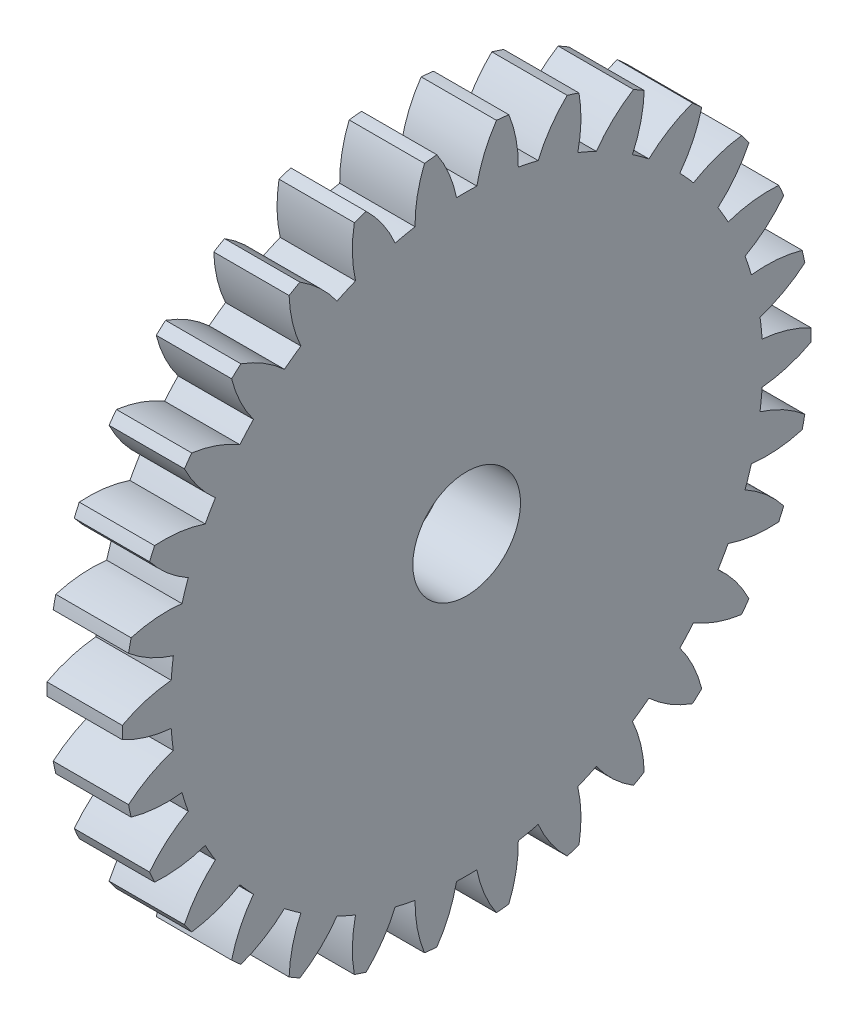
SolidWorks part; units mm, degrees
material "Cedar"
ref_plane "Plane1" through (0, 0, 0) normal (0, 0, 1) x (1, 0, 0)
ref_plane "Plane2" through (0, 0, 0) normal (0, 1, 0) x (1, 0, 0)
ref_plane "Plane3" through (0, 0, 0) normal (1, 0, 0) x (0, 0, -1)
sketch "HoldingSke" plane through (0, 0, 0) normal (0, 1, 0) x (1, 0, 0)
  line L0 (0, 0) -> (439.9409, -254)
  line L1 (-15, 0) -> (100, 0) construction
  line L2 (0, 0) -> (-2.1039, 2.3779)
  line L3 (0, 0) -> (-11.863, 4.5341)
  line L4 (0, 0) -> (7.479, 4.318)
  line L5 (0, 0) -> (-47.5972, -17.7524)
  line L6 (0, 0) -> (-3.6847, -2.4861)
  line L7 (-2.1039, 2.3779) -> (8.8308, 51.9871)
  line L8 (-76.2, 54.61) -> (-69.596, 54.61)
  line L9 (-71.009, 38.7566) -> (-53.1078, 45.2721)
  line L10 (-76.2, 71.12) -> (104.1128, 71.12)
  line L11 (0, 0) -> (-4.445, 0)
  line L12 (-76.2, 101.6) -> (-76.1492, 101.6)
  line L13 (24.9733, 27.94) -> (52.9518, 28.4284)
  line L14 (24.9733, 27.94) -> (25.0241, 27.9398)
  line L15 (24.9733, 27.94) -> (100.4021, 29.52)
  circle A0 centre (0, 0) radius 3.175
  circle A1 centre (0, 0) radius 17.4752
  circle A2 centre (0, 0) radius 38.1
  circle A3 centre (0, 0) radius 3.175
  dimension "MHD" = 34.9504
  dimension "Hub_dia" = 76.2
  dimension "Bore" = 6.35
  dimension "MBD" = 6.35
  dimension "Num_teeth" = 30
  dimension "Pitch_radius" = 180.3128
  dimension "Pitch" = 508
  dimension "Width" = 4.445
  dimension "Overall_len" = 50.8
  dimension "Show_teeth" = 30
  dimension "Thickness" = 4.445
  dimension "OAL" = 50.8001
  dimension "T_dim" = 6.604
  dimension "Ap" = 20
  dimension "H" = 19.05
  dimension "Backlash" = 0.0508
  dimension "Addendum_fac" = 1
  dimension "Dedendum_fac" = 1.2
  dimension "Clearance_fac" = 0.2
  dimension "Dedendum_add" = 0.0508
sketch "BasProSke" plane through (0, 0, 0) normal (0, 1, 0) x (1, 0, 0)
  line L0 (-10, 0) -> (60, 0) construction
  line L1 (0, 0) -> (0, 20.32)
  line L2 (0, 0) -> (4.445, 0)
  line L3 (4.445, 0) -> (4.445, 20.32)
  line L4 (4.445, 20.32) -> (0, 20.32)
  dimension "Diameter" = 40.64
  dimension "Thickness" = 4.445
revolve "Base-Revolve" add sketch "BasProSke" angle 360 about L0
sketch "TooCutSke" plane through (0, 0, 0) normal (1, 0, 0) x (0, 0, -1)
  line L1 (0, 0) -> (0, 107) construction
  line L2 (0, 0) -> (-1.0859, 19.019) construction
  line L3 (0, 0) -> (-3.978, 37.8482) construction
  line L4 (-1.0859, 19.019) -> (-1.989, 18.9241) construction
  arc A0 (0.5992, 17.4649) -> (-0.5992, 17.4649) centre (0, 0) ccw
  arc A1 (1.7751, 20.2678) -> (-1.7751, 20.2678) centre (0, 0) ccw
  circle A2 centre (0, 0) radius 19.05 construction
  circle A3 centre (0, 0) radius 17.9011 construction
  arc A4 (-0.5992, 17.4649) -> (-1.7751, 20.2678) centre (-8.0726, 15.9776) ccw
  arc A5 (1.7751, 20.2678) -> (0.5992, 17.4649) centre (8.0726, 15.9776) ccw
  dimension "Root_dia" = 34.9504
  dimension "Overcut_dia" = 40.6908
  dimension "Pitch_dia" = 38.1
  dimension "Base_dia" = 35.8023
  dimension "Flank_rad" = 7.62
  dimension "Half_ang" = 6
  dimension "Half_CT" = 0.9081
extrude "ToothCut" cut sketch "TooCutSke" along normal through all
fillet "Breaks" [suppressed] radius 0.0254
fillet "RootFillets" [suppressed] radius 0.3048
pattern_circular "TeethCuts" count 30 every 12 about axis through (-10, 0, 0) along (1, 0, 0) of "ToothCut", "RootFillets", "Breaks"
sketch "HubNeaOneSke" plane through (0, 0, 0) normal (-1, 0, 0) x (0, 0, 1)
  circle A0 centre (0, 0) radius 17.4752
  dimension "Diameter" = 34.9504
extrude "HubNearOne" [suppressed] add sketch "HubNeaOneSke" along normal blind 46.3551
sketch "HubNeaBotSke" plane through (0, 0, 0) normal (-1, 0, 0) x (0, 0, 1)
  circle A0 centre (0, 0) radius 17.4752
  dimension "Diameter" = 34.9504
extrude "HubNearBoth" [suppressed] add sketch "HubNeaBotSke" along normal blind 23.1775
ref_plane "FarPln" through (4.445, 0, 0) normal (1, 0, 0) x (0, 0, -1)
sketch "HubFarSke" plane through (4.445, 0, 0) normal (1, 0, 0) x (0, 0, -1)
  circle A0 centre (0, 0) radius 17.4752
  dimension "Diameter" = 34.9504
extrude "HubFar" [suppressed] add sketch "HubFarSke" along normal blind 23.1775
sketch "BorSke" plane through (0, 0, 0) normal (1, 0, 0) x (0, 0, -1)
  circle A0 centre (0, 0) radius 3.175
  dimension "Diameter" = 6.35
extrude "Bore" cut sketch "BorSke" along normal mid plane 101.6001
sketch "KeySke" plane through (0, 0, 0) normal (1, 0, 0) x (0, 0, -1)
  line L0 (-0.127, 0) -> (-0.127, 3.429)
  line L1 (-0.127, 3.429) -> (0.127, 3.429)
  line L2 (0.127, 3.429) -> (0.127, 0)
  line L3 (0, 0) -> (0, 34) construction
  line L4 (-0.127, 0) -> (0.127, 0)
  dimension "Offset" = 3.429
  dimension "Width" = 0.254
extrude "Keyway" [suppressed] cut sketch "KeySke" along normal mid plane 101.6001
pattern_circular "Keyway2" [suppressed] count 2 every 90 about axis through (-10, 0, 0) along (1, 0, 0)
sketch "Sketch2" plane through (0, 0, 0) normal (-1, 0, 0) x (0, 0, 1)
  circle A0 centre (0, 0) radius 19.05
  dimension "D1" = 38.1
equation "' \"Pitch@HoldingSke\" = 4"
equation "' \"Num_teeth@HoldingSke\" = 12"
equation "' \"Ap@HoldingSke\" =  20"
equation "' \"Width@HoldingSke\" = 0.5"
equation "' \"Hub_dia@HoldingSke\"= 1"
equation "' \"Overall_len@HoldingSke\" = 1.0"
equation "' \"Bore@HoldingSke\" = 0.75"
equation "' \"T_dim@HoldingSke\" = 0.85"
equation "' \"Width@KeySke\" = 0.25"
equation "' \"Show_teeth@HoldingSke\" = 13"
equation "' \"Backlash@HoldingSke\" = 0.009"
equation "' \"Addendum_fac@HoldingSke\" = 1.0"
equation "' \"Dedendum_fac@HoldingSke\" = 1.25"
equation "' \"Dedendum_add@HoldingSke\" = 0.00005"
equation "' \"Clearance_fac@HoldingSke\" = 0.25"
equation "' \"Pitch@HoldingSke\" = 0.5"
equation "' \"Num_teeth@HoldingSke\" = 23"
equation "' \"Show_teeth@HoldingSke\" = 23"
equation "' \"Backlash@HoldingSke\" = 0.0375"
equation "\"Overcut_dia@TooCutSke\" = (\"Num_teeth@HoldingSke\" + 2 * \"Addendum_fac@HoldingSke\") / \"Pitch@HoldingSke\" + 0.002"
equation "\"Pitch_dia@TooCutSke\" = \"Num_teeth@HoldingSke\" / \"Pitch@HoldingSke\""
equation "\"Base_dia@TooCutSke\" = \"Num_teeth@HoldingSke\" / \"Pitch@HoldingSke\" * cos((\"Ap@HoldingSke\"  * 3.14159265 / 180))"
equation "\"Root_dia@TooCutSke\" = (\"Num_teeth@HoldingSke\" + 2) / \"Pitch@HoldingSke\" - 2 * (\"Addendum_fac@HoldingSke\" + \"Dedendum_fac@HoldingSke\") / \"Pitch@HoldingSke\" - \"Dedendum_add@HoldingSke\" * 2"
equation "\"Half_ang@TooCutSke\" = 180 / \"Num_teeth@HoldingSke\""
equation "\"Half_CT@TooCutSke\" = \"Num_teeth@HoldingSke\" / \"Pitch@HoldingSke\" * sin((3.14159265 / 2 / \"Num_teeth@HoldingSke\")) / 2 - 7 * \"Backlash@HoldingSke\" / 4"
equation "\"Flank_rad@TooCutSke\" = \"Num_teeth@HoldingSke\" / \"Pitch@HoldingSke\" / 5"
equation "\"Radius@RootFillets\" = \"Clearance_fac@HoldingSke\" / \"Pitch@HoldingSke\" + \"Dedendum_add@HoldingSke\""
equation "\"Break_rad@Breaks\" = 0.02 / \"Pitch@HoldingSke\""
equation "\"Thickness@HoldingSke\" = \"Width@HoldingSke\""
equation "\"OAL@HoldingSke\" = \"Thickness@HoldingSke\""
equation "\"MHD@HoldingSke\" = (\"Num_teeth@HoldingSke\" + 2) / \"Pitch@HoldingSke\" - 2 * (\"Addendum_fac@HoldingSke\" + \"Dedendum_fac@HoldingSke\")  / \"Pitch@HoldingSke\" - \"Dedendum_add@HoldingSke\" * 2"
equation "\"MBD@HoldingSke\" = (\"Num_teeth@HoldingSke\" + 2) / \"Pitch@HoldingSke\" - 2 * (\"Addendum_fac@HoldingSke\" + \"Dedendum_fac@HoldingSke\")  / \"Pitch@HoldingSke\" - \"Dedendum_add@HoldingSke\" * 2 - 0.002"
equation "\"MHD@HoldingSke\" = ((sgn( \"MHD@HoldingSke\" - \"Hub_dia@HoldingSke\" )-1)*( \"MHD@HoldingSke\" - \"Hub_dia@HoldingSke\" ))/-2+ \"Hub_dia@HoldingSke\""
equation "\"MBD@HoldingSke\" = ((sgn( \"MBD@HoldingSke\" - \"Bore@HoldingSke\" )-1)*( \"MBD@HoldingSke\" - \"Bore@HoldingSke\" ))/-2+ \"Bore@HoldingSke\""
equation "\"OAL@HoldingSke\" = ((sgn( \"OAL@HoldingSke\" - \"Overall_len@HoldingSke\" )+1)*( \"OAL@HoldingSke\" - \"Overall_len@HoldingSke\" ))/2 + \"Overall_len@HoldingSke\" + 0.000002"
equation "\"Num_teeth@TeethCuts\" = int( \"Show_teeth@HoldingSke\" ) + 1"
equation "\"Num_teeth@TeethCuts\" = ((sgn( \"Num_teeth@TeethCuts\" - \"Num_teeth@HoldingSke\" )-1)*( \"Num_teeth@TeethCuts\" - \"Num_teeth@HoldingSke\" ))/-2+ \"Num_teeth@HoldingSke\""
equation "\"Num_teeth@TeethCuts\" = ((sgn( \"Num_teeth@TeethCuts\" - 2.0)+1)*( \"Num_teeth@TeethCuts\" - 2.0))/2 +2.0"
equation "\"Angle@TeethCuts\" = 360.0 / \"Num_teeth@HoldingSke\""
equation "\"Diameter@BasProSke\" = (\"Num_teeth@HoldingSke\" + 2 * \"Addendum_fac@HoldingSke\") / \"Pitch@HoldingSke\""
equation "\"Thickness@BasProSke\"  = \"Thickness@HoldingSke\""
equation "' \"Fillet_rad@BasProSke\" =  \"Thickness@HoldingSke\" * 0.05"
equation "\"MHD@HoldingSke\" = ((sgn( \"MHD@HoldingSke\" - \"Root_dia@TooCutSke\" )-1)*( \"MHD@HoldingSke\" - \"Root_dia@TooCutSke\" ))/-2+ \"Root_dia@TooCutSke\""
equation "\"Diameter@HubNeaOneSke\" = \"MHD@HoldingSke\""
equation "\"Length@HubNearOne\" = \"OAL@HoldingSke\" - \"Thickness@BasProSke\""
equation "\"Diameter@HubNeaBotSke\" = \"MHD@HoldingSke\""
equation "\"Length@HubNearBoth\" = ( \"OAL@HoldingSke\" - \"Thickness@BasProSke\" ) / 2.0"
equation "\"Thickness@FarPln\" = \"Thickness@BasProSke\""
equation "\"Diameter@HubFarSke\" = \"MHD@HoldingSke\""
equation "\"Length@HubFar\" = ( \"OAL@HoldingSke\" - \"Thickness@BasProSke\" ) / 2.0"
equation "\"Diameter@BorSke\" = \"MBD@HoldingSke\""
equation "\"D1@Bore\" = \"OAL@HoldingSke\" * 2.0"
equation "\"D1@Keyway\" = \"OAL@HoldingSke\" * 2.0"
equation "\"Offset@KeySke\" = \"T_dim@HoldingSke\" - \"MBD@HoldingSke\" / 2.0"
